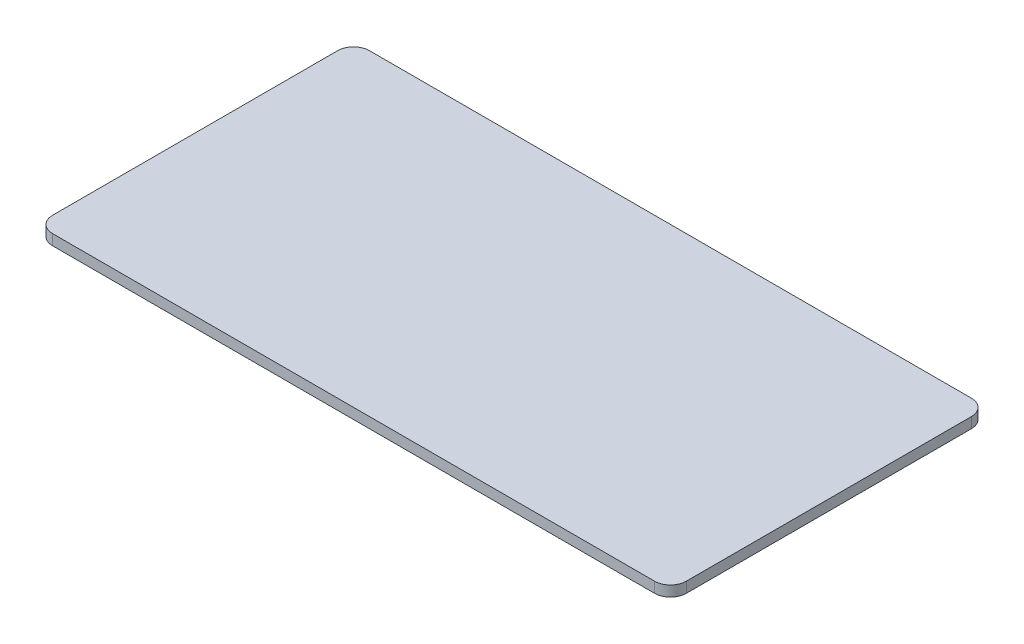
SolidWorks part; units mm, degrees
ref_plane "Front Plane" through (0, 0, 0) normal (0, 0, 1) x (1, 0, 0)
ref_plane "Top Plane" through (0, 0, 0) normal (0, 1, 0) x (1, 0, 0)
ref_plane "Right Plane" through (0, 0, 0) normal (1, 0, 0) x (0, 0, -1)
sketch "Sketch1" plane through (0, 0, 0) normal (0, 1, 0) x (1, 0, 0)
  line L1 (-513.9721, -307.3197) -> (686.0279, -307.3197)
  line L2 (-513.9721, -307.3197) -> (-513.9721, 292.6803)
  line L3 (-513.9721, 292.6803) -> (686.0279, 292.6803)
  line L4 (686.0279, -307.3197) -> (686.0279, 292.6803)
  dimension "D1" = 1200
  dimension "D2" = 600
extrude "Boss-Extrude1" add sketch "Sketch1" along normal blind 20
fillet "Fillet1" radius 30 4 edges at (-513.9721, 10, -292.6803) (-513.9721, 10, 307.3197) (686.0279, 10, -292.6803) (686.0279, 10, 307.3197)
